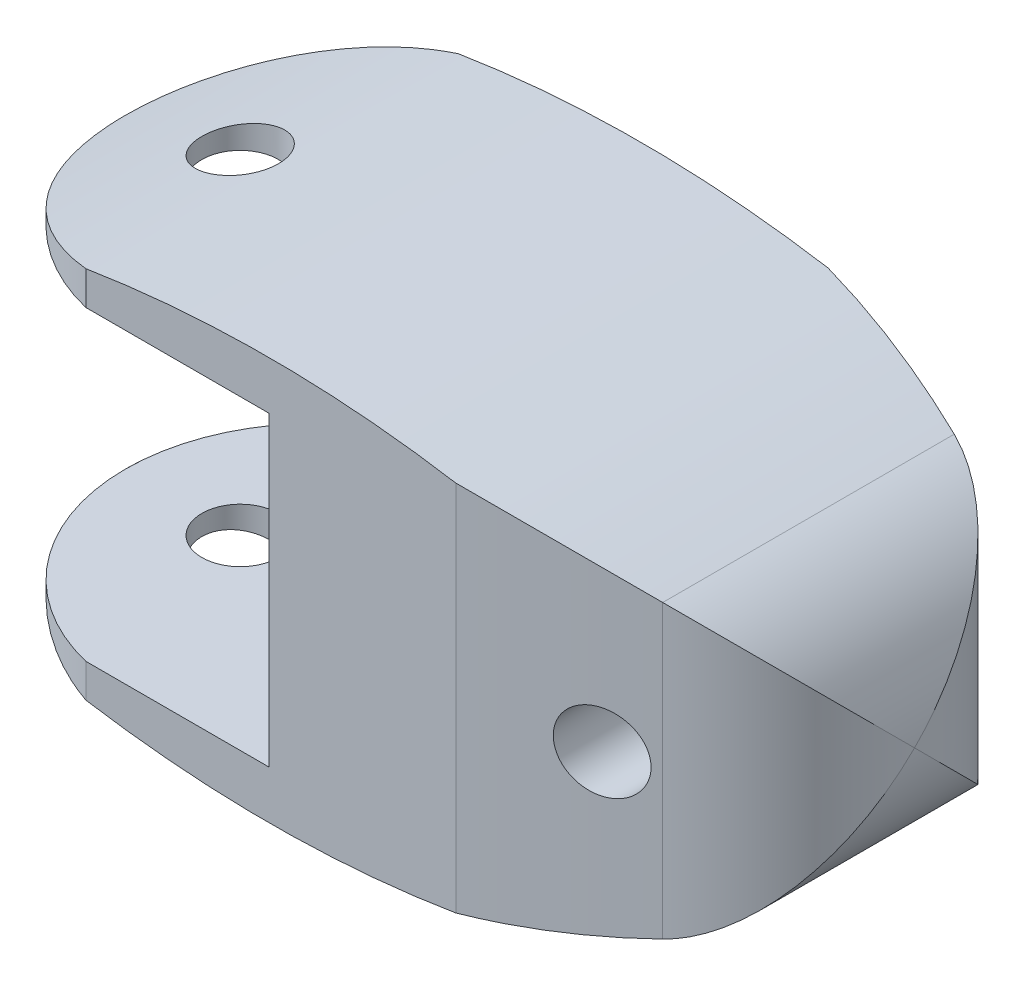
SolidWorks part; units mm, degrees
ref_plane "Alzado" through (0, 0, 0) normal (0, 0, 1) x (1, 0, 0)
ref_plane "Planta" through (0, 0, 0) normal (0, 1, 0) x (1, 0, 0)
ref_plane "Vista lateral" through (0, 0, 0) normal (1, 0, 0) x (0, 0, -1)
sketch "Croquis1" plane through (0, 0, 0) normal (0, 0, 1) x (1, 0, 0)
  line L0 (-4, 0) -> (4, 0) construction
  line L3 (0, -89.1512) -> (0, 4368.4077) construction
  arc A0 (-4.6154, 1.903) -> (-4.6154, -1.903) centre (-4, 0) ccw
  arc A1 (4.6154, -1.903) -> (4.6154, 1.903) centre (4, 0) ccw
  arc A2 (-4.6154, 1.903) -> (4.6154, 1.903) centre (0, -12.3693) cw
  arc A3 (-4.6154, -1.903) -> (4.6154, -1.903) centre (0, 12.3693) ccw
  circle A6 centre (4, 0) radius 0.5
  point P3 (0, 0)
  dimension "D1" = 12
  dimension "D2" = 2
  dimension "D3" = 15
  dimension "D4" = 1
extrude "Saliente-Extruir1" add sketch "Croquis1" along normal blind 6
sketch "Croquis7" plane through (0, 0, 0) normal (0, 1, 0) x (1, 0, 0)
  line L0 (-4, -3) -> (4, -3) construction
  line L3 (0, -89.1512) -> (0, 4368.4077) construction
  line L4 (4.6154, -6) -> (4.6154, 0) construction
  line L5 (6, -6) -> (6, 0) construction
  line L7 (-6, 0) -> (6, 0)
  line L8 (6, 0) -> (6, -3)
  line L9 (6, -3) -> (6, -6)
  line L10 (6, -6) -> (-6, -6)
  line L11 (-6, -6) -> (-4.6154, -6) construction
  line L12 (-6, -6) -> (-6, -3)
  line L13 (-6, 0) -> (-6, -3)
  line L14 (-2.4413, -5.4307) -> (2.4413, -5.4307)
  line L15 (-2.4413, -0.5693) -> (2.4413, -0.5693)
  arc A0 (-4.6154, -1.097) -> (-4.6154, -4.903) centre (-4, -3) ccw
  arc A1 (4.6154, -4.903) -> (4.6154, -1.097) centre (4, -3) ccw
  arc A2 (-4.6154, -1.097) -> (-2.4413, -0.5693) centre (0, -15.3693) cw
  arc A3 (-4.6154, -4.903) -> (-2.4413, -5.4307) centre (0, 9.3693) ccw
  arc A4 (2.4413, -5.4307) -> (4.6154, -4.903) centre (0, 9.3693) ccw
  arc A5 (2.4413, -0.5693) -> (4.6154, -1.097) centre (0, -15.3693) cw
  point P3 (0, -3)
  point P11 (4.6154, -3)
  dimension "D1" = 12
  dimension "D2" = 2
  dimension "D3" = 15
  dimension "D4" = 0.2
extrude "Cortar-Extruir6" cut sketch "Croquis7" against normal through all both and the other way through all contours A0 A2 A1 L8 L7 L13 | A3 A0 L12 L10 L9 A1
sketch "Croquis3" plane through (0, 0, 0) normal (0, 0, 1) x (1, 0, 0)
  line L0 (-3, 0) -> (0, 0) construction
  line L1 (0, -2) -> (-6, -2)
  line L2 (0, -2) -> (0, 2)
  line L3 (0, 2) -> (-6, 2)
  line L4 (-6, -2) -> (-6, 2)
  line L5 (0, -2) -> (-6, 2) construction
  line L6 (0, 2) -> (-6, -2) construction
  arc A1 (-6, 0) -> (-4.6154, -1.903) centre (-4, 0) ccw construction
  point P0 (-3, 0)
  dimension "D1" = 4
extrude "Cortar-Extruir2" cut sketch "Croquis3" along normal through all
sketch "Croquis4" plane through (0, 0, 0) normal (0, 1, 0) x (1, 0, 0)
  line L2 (-4.3038, -1) -> (-4.3038, -5) construction
  line L8 (-4.3038, -1) -> (-4.3038, -3)
  line L9 (-4.3038, -3) -> (-4.3038, -5)
  arc A3 (-2.1647, -0.5263) -> (-2.1647, -5.4737) centre (-1.804, -3) ccw
  arc A4 (-2.4413, -0.5693) -> (-4.3038, -1) centre (0, -15.3693) ccw construction
  arc A5 (-4.3038, -5) -> (-2.4413, -5.4307) centre (0, 9.3693) ccw construction
  arc A7 (-2.1647, -0.5263) -> (-4.3038, -1) centre (0, -15.3693) ccw
  arc A8 (-4.3038, -5) -> (-2.1647, -5.4737) centre (0, 9.3693) ccw
extrude "Cortar-Extruir7" cut sketch "Croquis4" against normal through all both and the other way through all contours A3 A7 L8 | L9 A8 A3
sketch "Croquis2" plane through (0, 0, 0) normal (0, 1, 0) x (1, 0, 0)
  line L0 (-2.8038, -5.2912) -> (-2.8038, -0.7088) construction
  circle A0 centre (-2.8038, -3) radius 0.5
  arc A1 (-2.3879, -0.5693) -> (-4.3038, -3) centre (-1.804, -3) ccw construction
  arc A2 (-4.3038, -3) -> (-2.3879, -5.4307) centre (-1.804, -3) ccw construction
  point P6 (-2.8038, -3)
  dimension "D1" = 1
  dimension "D2" = 1.5
extrude "Cortar-Extruir1" cut sketch "Croquis2" against normal through all both and the other way through all
